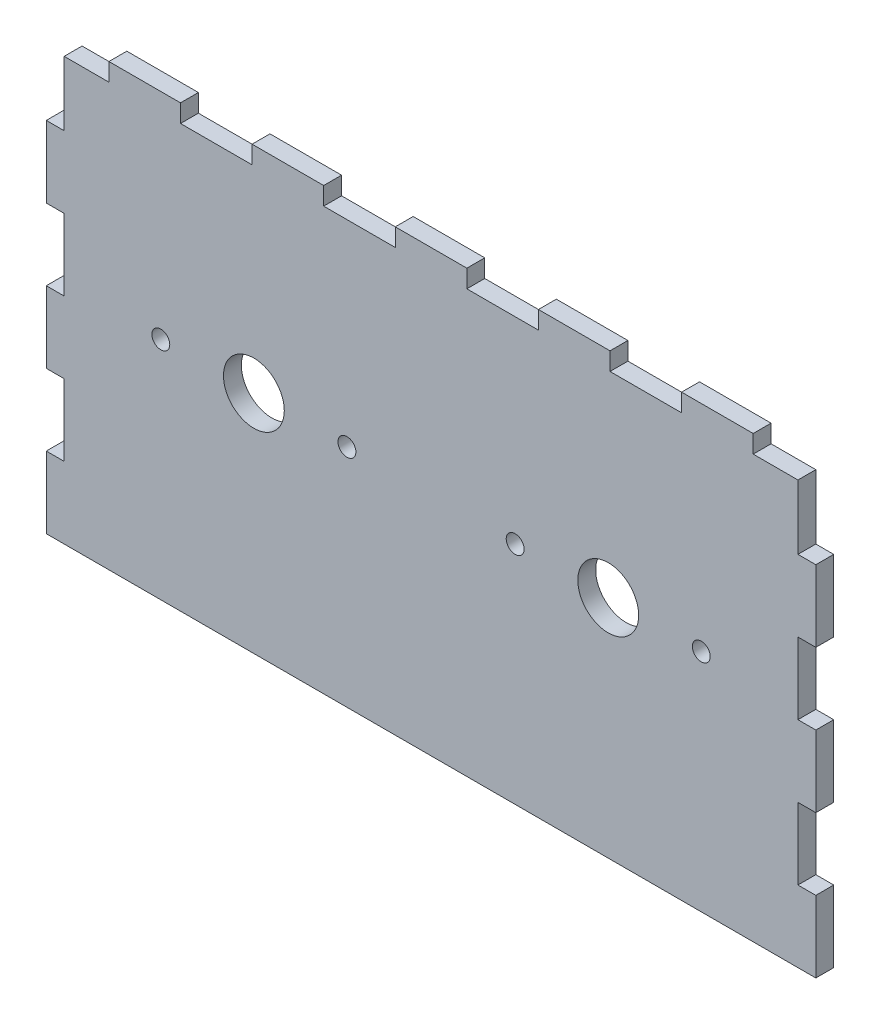
SolidWorks part; units mm, degrees
ref_plane "정면" through (0, 0, 0) normal (0, 0, 1) x (1, 0, 0)
ref_plane "윗면" through (0, 0, 0) normal (0, 1, 0) x (1, 0, 0)
ref_plane "우측면" through (0, 0, 0) normal (1, 0, 0) x (0, 0, -1)
sketch "스케치1" plane through (0, 0, 0) normal (0, 0, 1) x (1, 0, 0)
  line L0 (-49.5, 80.911) -> (-49.5, -78.9061) construction
  line L1 (-102.5, 59) -> (102.5, 59)
  line L2 (-102.5, 59) -> (-102.5, -59)
  line L3 (-102.5, -59) -> (102.5, -59)
  line L4 (102.5, 59) -> (102.5, -59)
  line L5 (-102.5, 59) -> (102.5, -59) construction
  line L6 (-102.5, -59) -> (102.5, 59) construction
  line L7 (49.5, 64.3355) -> (49.5, -72.4738) construction
  line L8 (0, 68.0997) -> (0, -64.9282) construction
  circle A0 centre (49.5, 4) radius 8.5
  circle A1 centre (-49.5, 4) radius 8.5
  circle A4 centre (-75.5, 4) radius 2.5
  circle A5 centre (-23.5, 4) radius 2.5
  circle A6 centre (23.5, 4) radius 2.5
  circle A7 centre (75.5, 4) radius 2.5
  point P0 (0, 0)
  dimension "D3" = 17
  dimension "D8" = 52
  dimension "D9" = 5
  dimension "D1" = 118
  dimension "D2" = 205
  dimension "D4" = 55
  dimension "D5" = 55
  dimension "D6" = 49.5
  dimension "D7" = 49.5
extrude "보스-돌출1" add sketch "스케치1" along normal blind 5
sketch "스케치2" plane through (0, 0, 5) normal (0, 0, 1) x (1, 0, 0)
  line L1 (-102.5, -59) -> (-107.5, -59)
  line L2 (-102.5, -59) -> (-102.5, -39)
  line L3 (-102.5, -39) -> (-107.5, -39)
  line L4 (-107.5, -59) -> (-107.5, -39)
  dimension "D1" = 5
  dimension "D2" = 20
extrude "보스-돌출2" add sketch "스케치2" against normal up to surface (5 mm away) up to face at (0, 0, 0)
pattern_linear "선형 패턴1" count 3 spacing 40 along (0, 1, 0) of "보스-돌출2"
mirror "대칭 복사1" about plane through (0, 0, 0) normal (1, 0, 0) of "선형 패턴1", "보스-돌출2"
sketch "스케치3" plane through (0, 0, 5) normal (0, 0, 1) x (1, 0, 0)
  line L0 (102.5, 59) -> (-102.5, 59) construction
  line L1 (10, 59) -> (-10, 59)
  line L2 (10, 59) -> (10, 64)
  line L3 (10, 64) -> (-10, 64)
  line L4 (-10, 59) -> (-10, 64)
  line L5 (0, 197.1917) -> (0, -69.1917) construction
  point P9 (0, 64)
  dimension "D1" = 20
  dimension "D2" = 5
extrude "보스-돌출3" add sketch "스케치3" against normal up to surface (5 mm away) up to face at (0, 0.8333, 0)
pattern_linear "선형 패턴2" count 3 spacing 40 along (1, 0, 0) of "보스-돌출3"
pattern_linear "선형 패턴3" count 3 spacing 40 along (-1, 0, 0) of "보스-돌출3"
